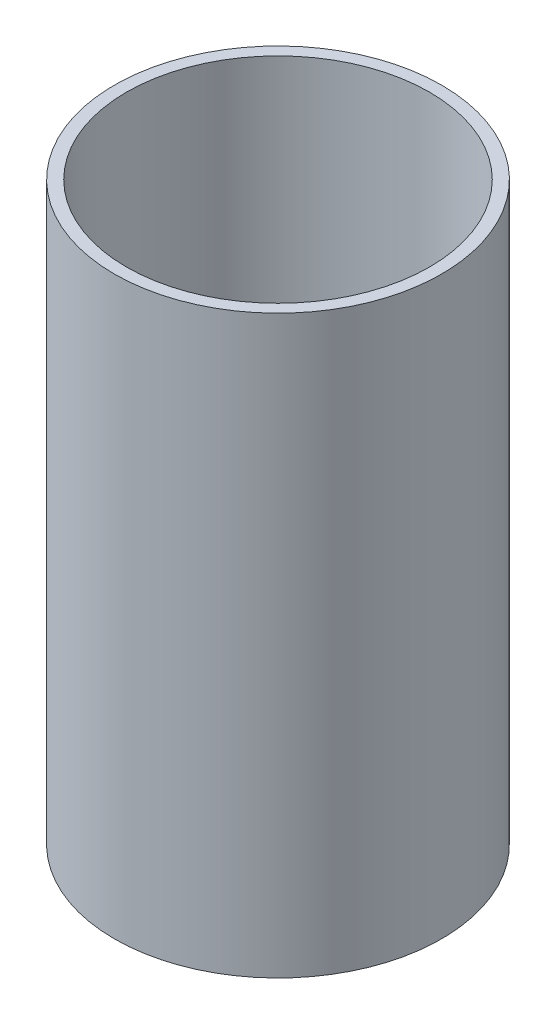
SolidWorks part; units mm, degrees
material "Thornel Mat VMA"
ref_plane "Front Plane" through (0, 0, 0) normal (0, 0, 1) x (1, 0, 0)
ref_plane "Top Plane" through (0, 0, 0) normal (0, 1, 0) x (1, 0, 0)
ref_plane "Right Plane" through (0, 0, 0) normal (1, 0, 0) x (0, 0, -1)
sketch "Sketch2" plane through (0, 0, 0) normal (0, 1, 0) x (1, 0, 0)
  circle A0 centre (0, 0) radius 13.716
  circle A1 centre (0, 0) radius 12.7
  dimension "D1" = 25.4
  dimension "D2" = 1.016
extrude "Boss-Extrude1" add sketch "Sketch2" along normal blind 48.26
